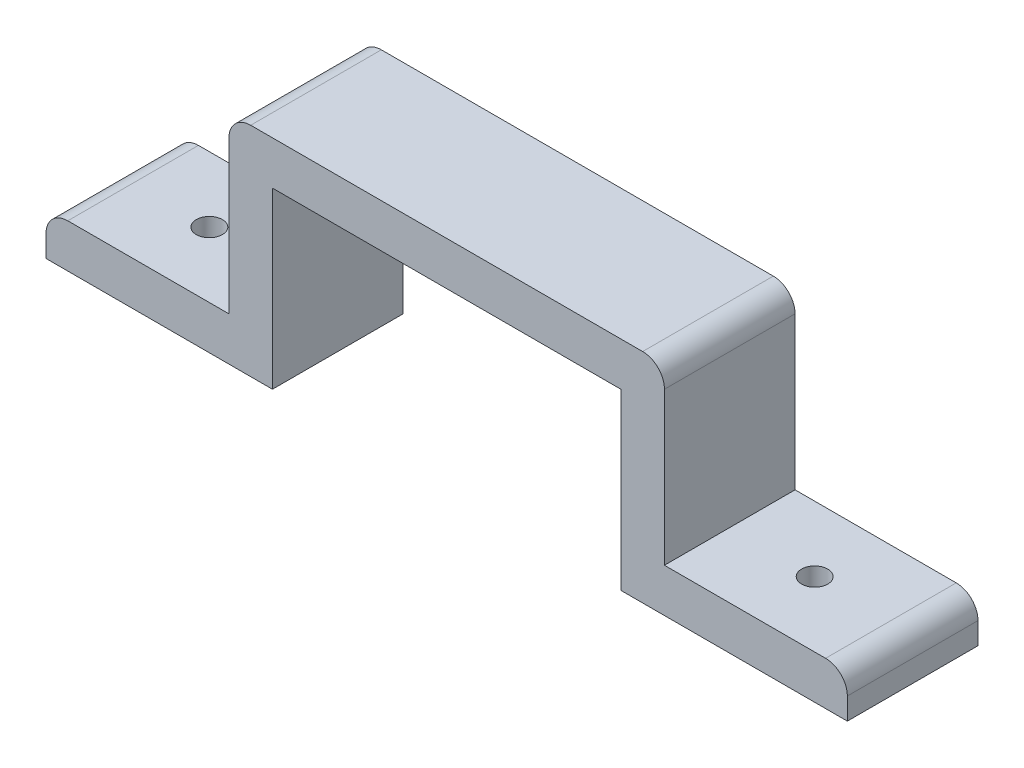
SolidWorks part; units mm, degrees
ref_plane "Front Plane" through (0, 0, 0) normal (0, 0, 1) x (1, 0, 0)
ref_plane "Top Plane" through (0, 0, 0) normal (0, 1, 0) x (1, 0, 0)
ref_plane "Right Plane" through (0, 0, 0) normal (1, 0, 0) x (0, 0, -1)
sketch "Sketch1" plane through (0, 0, 0) normal (0, 0, 1) x (1, 0, 0)
  line L0 (0, 0) -> (0, 20) construction
  line L1 (20, 20) -> (-20, 20)
  line L2 (-20, 20) -> (-20, 0)
  line L3 (-20, 0) -> (-46, 0)
  line L4 (-46, 0) -> (-46, 5)
  line L5 (-46, 5) -> (-25, 5)
  line L6 (-25, 5) -> (-25, 25)
  line L7 (25, 5) -> (25, 25)
  line L8 (46, 5) -> (25, 5)
  line L9 (46, 0) -> (46, 5)
  line L10 (20, 0) -> (46, 0)
  line L11 (20, 20) -> (20, 0)
  line L12 (-25, 25) -> (25, 25)
  dimension "D1" = 20
  dimension "D2" = 25
  dimension "D3" = 20
  dimension "D4" = 25
  dimension "D5" = 5
  dimension "D6" = 46
extrude "Boss-Extrude1" add sketch "Sketch1" along normal blind 15
fillet "Fillet1" radius 2.5 4 edges at (-25, 25, 7.5) (25, 25, 7.5) (-46, 5, 7.5) (46, 5, 7.5)
sketch "Sketch2" plane through (0, 5, 0) normal (0, 1, 0) x (1, 0, 0)
  line L6 (0, 0) -> (0, -15) construction
  line L7 (22.5, -15) -> (-22.5, -15) construction
  circle A0 centre (34.75, -7.5) radius 1.5
  circle A1 centre (-34.75, -7.5) radius 1.5
  dimension "D1" = 3
  dimension "D2" = 3
  dimension "D3" = 34.75
  dimension "D4" = 8.75
  dimension "D5" = 7.5
extrude "Cut-Extrude1" cut sketch "Sketch2" against normal up to surface (5 mm away) up to face at (33, 0, 7.5)
